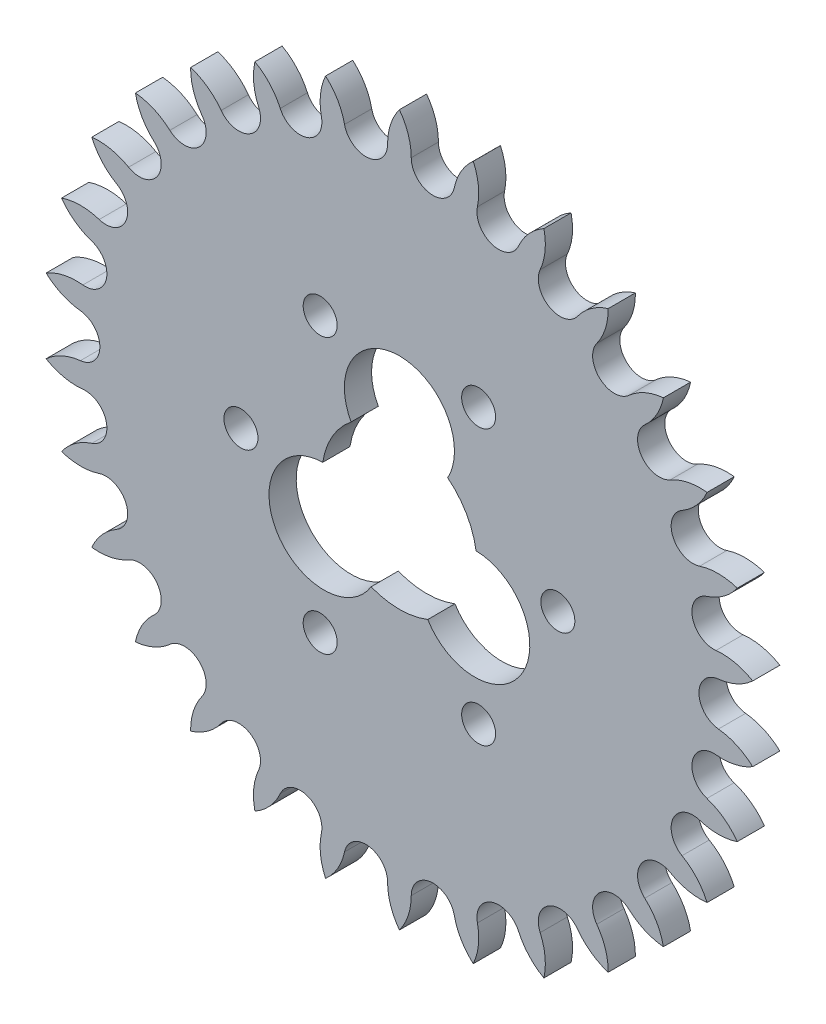
SolidWorks part; units mm, degrees
material "6061-T6 (SS)"
ref_plane "Front Plane" through (0, 0, 0) normal (0, 0, 1) x (1, 0, 0)
ref_plane "Top Plane" through (0, 0, 0) normal (0, 1, 0) x (1, 0, 0)
ref_plane "Right Plane" through (0, 0, 0) normal (1, 0, 0) x (0, 0, -1)
sketch "Sketch1" plane through (0, 0, 0) normal (0, 0, 1) x (1, 0, 0)
  arc A1 (-2.7623, 74.614) -> (0, 82.9535) centre (11.2077, 74.614) cw
  arc A2 (0, 82.9535) -> (2.7623, 74.614) centre (-11.2077, 74.614) cw
  arc A3 (2.7623, 74.614) -> (12.8112, 73.5578) centre (7.8423, 74.614) ccw
  arc A5 (12.8112, 73.5578) -> (17.247, 81.1408) centre (26.476, 70.6533) cw
  arc A6 (17.247, 81.1408) -> (18.215, 72.4092) centre (4.5503, 75.3138) cw
  arc A7 (18.215, 72.4092) -> (27.8248, 69.2868) centre (23.184, 71.353) ccw
  arc A8 (27.8248, 69.2868) -> (33.7402, 75.7818) centre (40.587, 63.6047) cw
  arc A9 (33.7402, 75.7818) -> (32.8717, 67.0398) centre (20.1095, 72.7219) cw
  arc A10 (32.8717, 67.0398) -> (41.6223, 61.9876) centre (37.5125, 64.9736) ccw
  arc A11 (41.6223, 61.9876) -> (48.7589, 67.1108) centre (52.9243, 53.7763) cw
  arc A12 (48.7589, 67.1108) -> (46.0917, 58.7404) centre (34.7898, 66.9518) cw
  arc A13 (46.0917, 58.7404) -> (53.6007, 51.9793) centre (50.2015, 55.7545) ccw
  arc A14 (53.6007, 51.9793) -> (61.6465, 55.5067) centre (62.9485, 41.5975) cw
  arc A15 (61.6465, 55.5067) -> (57.2973, 47.8738) centre (47.9496, 58.2555) cw
  arc A16 (57.2973, 47.8738) -> (63.2365, 39.6992) centre (60.6965, 44.0986) ccw
  arc A17 (63.2365, 39.6992) -> (71.8399, 41.4768) centre (70.2215, 27.6008) cw
  arc A18 (71.8399, 41.4768) -> (65.9988, 34.9148) centre (59.0138, 47.0132) cw
  arc A19 (65.9988, 34.9148) -> (70.1086, 25.6841) centre (68.5388, 30.5154) ccw
  arc A20 (70.1086, 25.6841) -> (78.8935, 25.634) centre (74.4255, 12.3978) cw
  arc A21 (78.8935, 25.634) -> (71.8157, 20.4299) centre (67.4988, 33.7162) cw
  arc A22 (71.8157, 20.4299) -> (73.9165, 10.5464) centre (73.3855, 15.5986) ccw
  arc A23 (73.9165, 10.5464) -> (82.4991, 8.671) centre (75.3768, -3.3471) cw
  arc A24 (82.4991, 8.671) -> (74.494, 5.0522) centre (73.0338, 18.9456) cw
  arc A25 (74.494, 5.0522) -> (74.494, -5.0522) centre (75.025, 0) ccw
  arc A26 (74.494, -5.0522) -> (82.4991, -8.671) centre (73.0338, -18.9456) cw
  arc A27 (82.4991, -8.671) -> (73.9165, -10.5464) centre (75.3768, 3.3471) cw
  arc A28 (73.9165, -10.5464) -> (71.8157, -20.4299) centre (73.3855, -15.5986) ccw
  arc A29 (71.8157, -20.4299) -> (78.8935, -25.634) centre (67.4988, -33.7162) cw
  arc A30 (78.8935, -25.634) -> (70.1086, -25.6841) centre (74.4255, -12.3978) cw
  arc A31 (70.1086, -25.6841) -> (65.9988, -34.9148) centre (68.5388, -30.5154) ccw
  arc A32 (65.9988, -34.9148) -> (71.8399, -41.4768) centre (59.0138, -47.0132) cw
  arc A33 (71.8399, -41.4768) -> (63.2365, -39.6992) centre (70.2215, -27.6008) cw
  arc A34 (63.2365, -39.6992) -> (57.2973, -47.8738) centre (60.6965, -44.0986) ccw
  arc A35 (57.2973, -47.8738) -> (61.6465, -55.5067) centre (47.9496, -58.2555) cw
  arc A36 (61.6465, -55.5067) -> (53.6007, -51.9793) centre (62.9485, -41.5975) cw
  arc A37 (53.6007, -51.9793) -> (46.0917, -58.7404) centre (50.2015, -55.7545) ccw
  arc A38 (46.0917, -58.7404) -> (48.7589, -67.1108) centre (34.7898, -66.9518) cw
  arc A39 (48.7589, -67.1108) -> (41.6223, -61.9876) centre (52.9243, -53.7763) cw
  arc A40 (41.6223, -61.9876) -> (32.8717, -67.0398) centre (37.5125, -64.9736) ccw
  arc A41 (32.8717, -67.0398) -> (33.7402, -75.7818) centre (20.1095, -72.7219) cw
  arc A42 (33.7402, -75.7818) -> (27.8248, -69.2868) centre (40.587, -63.6047) cw
  arc A43 (27.8248, -69.2868) -> (18.215, -72.4092) centre (23.184, -71.353) ccw
  arc A44 (18.215, -72.4092) -> (17.247, -81.1408) centre (4.5503, -75.3138) cw
  arc A45 (17.247, -81.1408) -> (12.8112, -73.5578) centre (26.476, -70.6533) cw
  arc A46 (12.8112, -73.5578) -> (2.7623, -74.614) centre (7.8423, -74.614) ccw
  arc A47 (2.7623, -74.614) -> (0, -82.9535) centre (-11.2077, -74.614) cw
  arc A48 (0, -82.9535) -> (-2.7623, -74.614) centre (11.2077, -74.614) cw
  arc A49 (-2.7623, -74.614) -> (-12.8112, -73.5578) centre (-7.8423, -74.614) ccw
  arc A50 (-12.8112, -73.5578) -> (-17.247, -81.1408) centre (-26.476, -70.6533) cw
  arc A51 (-17.247, -81.1408) -> (-18.215, -72.4092) centre (-4.5503, -75.3138) cw
  arc A52 (-18.215, -72.4092) -> (-27.8248, -69.2868) centre (-23.184, -71.353) ccw
  arc A53 (-27.8248, -69.2868) -> (-33.7402, -75.7818) centre (-40.587, -63.6047) cw
  arc A54 (-33.7402, -75.7818) -> (-32.8717, -67.0398) centre (-20.1095, -72.7219) cw
  arc A55 (-32.8717, -67.0398) -> (-41.6223, -61.9876) centre (-37.5125, -64.9736) ccw
  arc A56 (-41.6223, -61.9876) -> (-48.7589, -67.1108) centre (-52.9243, -53.7763) cw
  arc A57 (-48.7589, -67.1108) -> (-46.0917, -58.7404) centre (-34.7898, -66.9518) cw
  arc A58 (-46.0917, -58.7404) -> (-53.6007, -51.9793) centre (-50.2015, -55.7545) ccw
  arc A59 (-53.6007, -51.9793) -> (-61.6465, -55.5067) centre (-62.9485, -41.5975) cw
  arc A60 (-61.6465, -55.5067) -> (-57.2973, -47.8738) centre (-47.9496, -58.2555) cw
  arc A61 (-57.2973, -47.8738) -> (-63.2365, -39.6992) centre (-60.6965, -44.0986) ccw
  arc A62 (-63.2365, -39.6992) -> (-71.8399, -41.4768) centre (-70.2215, -27.6008) cw
  arc A63 (-71.8399, -41.4768) -> (-65.9988, -34.9148) centre (-59.0138, -47.0132) cw
  arc A64 (-65.9988, -34.9148) -> (-70.1086, -25.6841) centre (-68.5388, -30.5154) ccw
  arc A65 (-70.1086, -25.6841) -> (-78.8935, -25.634) centre (-74.4255, -12.3978) cw
  arc A66 (-78.8935, -25.634) -> (-71.8157, -20.4299) centre (-67.4988, -33.7162) cw
  arc A67 (-71.8157, -20.4299) -> (-73.9165, -10.5464) centre (-73.3855, -15.5986) ccw
  arc A68 (-73.9165, -10.5464) -> (-82.4991, -8.671) centre (-75.3768, 3.3471) cw
  arc A69 (-82.4991, -8.671) -> (-74.494, -5.0522) centre (-73.0338, -18.9456) cw
  arc A70 (-74.494, -5.0522) -> (-74.494, 5.0522) centre (-75.025, 0) ccw
  arc A71 (-74.494, 5.0522) -> (-82.4991, 8.671) centre (-73.0338, 18.9456) cw
  arc A72 (-82.4991, 8.671) -> (-73.9165, 10.5464) centre (-75.3768, -3.3471) cw
  arc A73 (-73.9165, 10.5464) -> (-71.8157, 20.4299) centre (-73.3855, 15.5986) ccw
  arc A74 (-71.8157, 20.4299) -> (-78.8935, 25.634) centre (-67.4988, 33.7162) cw
  arc A75 (-78.8935, 25.634) -> (-70.1086, 25.6841) centre (-74.4255, 12.3978) cw
  arc A76 (-70.1086, 25.6841) -> (-65.9988, 34.9148) centre (-68.5388, 30.5154) ccw
  arc A77 (-65.9988, 34.9148) -> (-71.8399, 41.4768) centre (-59.0138, 47.0132) cw
  arc A78 (-71.8399, 41.4768) -> (-63.2365, 39.6992) centre (-70.2215, 27.6008) cw
  arc A79 (-63.2365, 39.6992) -> (-57.2973, 47.8738) centre (-60.6965, 44.0986) ccw
  arc A80 (-57.2973, 47.8738) -> (-61.6465, 55.5067) centre (-47.9496, 58.2555) cw
  arc A81 (-61.6465, 55.5067) -> (-53.6007, 51.9793) centre (-62.9485, 41.5975) cw
  arc A82 (-53.6007, 51.9793) -> (-46.0917, 58.7404) centre (-50.2015, 55.7545) ccw
  arc A83 (-46.0917, 58.7404) -> (-48.7589, 67.1108) centre (-34.7898, 66.9518) cw
  arc A84 (-48.7589, 67.1108) -> (-41.6223, 61.9876) centre (-52.9243, 53.7763) cw
  arc A85 (-41.6223, 61.9876) -> (-32.8717, 67.0398) centre (-37.5125, 64.9736) ccw
  arc A86 (-32.8717, 67.0398) -> (-33.7402, 75.7818) centre (-20.1095, 72.7219) cw
  arc A87 (-33.7402, 75.7818) -> (-27.8248, 69.2868) centre (-40.587, 63.6047) cw
  arc A88 (-27.8248, 69.2868) -> (-18.215, 72.4092) centre (-23.184, 71.353) ccw
  arc A89 (-18.215, 72.4092) -> (-17.247, 81.1408) centre (-4.5503, 75.3138) cw
  arc A90 (-17.247, 81.1408) -> (-12.8112, 73.5578) centre (-26.476, 70.6533) cw
  arc A91 (-12.8112, 73.5578) -> (-2.7623, 74.614) centre (-7.8423, 74.614) ccw
  circle A92 centre (0, 0) radius 69.945 construction
  circle A95 centre (0, 0) radius 82.9535 construction
  circle A96 centre (0, 0) radius 74.6651 construction
  dimension "D1" = 5.5245
  dimension "D3" = 13.97
  dimension "D4" = 5.08
extrude "Boss-Extrude1" add sketch "Sketch1" along normal blind 6.35
sketch "Sketch2" plane through (0, 0, 6.35) normal (0, 0, 1) x (1, 0, 0)
  line L0 (-37, 0) -> (-18.5, 32.0429) construction
  line L1 (-34.2507, -13.2992) -> (-3.5906, 39.8056) construction
  arc A1 (-11.277, 14.1545) -> (-17.8966, 2.6889) centre (0, 0) ccw
  arc A2 (11.277, 14.1545) -> (-11.277, 14.1545) centre (0, 20.32) ccw
  arc A3 (6.6196, -16.8434) -> (17.8966, 2.6889) centre (17.5976, -10.16) ccw
  arc A4 (-17.8966, 2.6889) -> (-6.6196, -16.8434) centre (-17.5976, -10.16) ccw
  arc A5 (-6.6196, -16.8434) -> (6.6196, -16.8434) centre (0, 0) ccw
  arc A6 (17.8966, 2.6889) -> (11.277, 14.1545) centre (0, 0) ccw
  circle A7 centre (-37, 0) radius 3.9687
  circle A8 centre (-18.5, 32.0429) radius 3.9688
  circle A9 centre (18.5, 32.0429) radius 3.9687
  circle A10 centre (37, 0) radius 3.9688
  circle A11 centre (18.5, -32.0429) radius 3.9688
  circle A12 centre (-18.5, -32.0429) radius 3.9688
  circle A13 centre (0, 0) radius 33.1724 construction
  point P12 (0, 0)
  point P27 (0, 0)
  dimension "D1" = 36.195
  dimension "D2" = 25.7048
  dimension "D4" = 7.9375
  dimension "D7" = 66.3448
  dimension "D6" = 74
  dimension "D3" = 3
  dimension "D5" = 6
extrude "Cut-Extrude1" cut sketch "Sketch2" against normal through all
